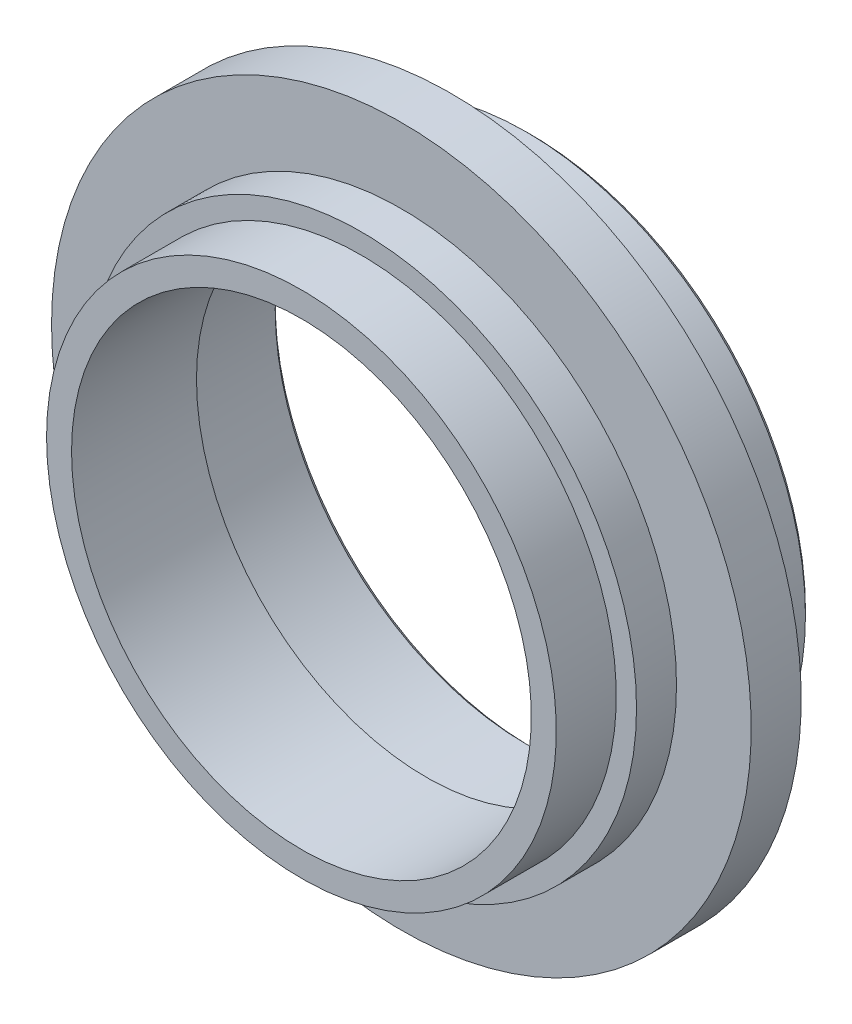
SolidWorks part; units mm, degrees
ref_plane "Front Plane" through (0, 0, 0) normal (0, 0, 1) x (1, 0, 0)
ref_plane "Top Plane" through (0, 0, 0) normal (0, 1, 0) x (1, 0, 0)
ref_plane "Right Plane" through (0, 0, 0) normal (1, 0, 0) x (0, 0, -1)
sketch "Sketch1" plane through (0, 0, 0) normal (0, 1, 0) x (1, 0, 0)
  line L0 (0, 99.2979) -> (0, -58.5521) construction
  line L1 (-100.4208, 0) -> (85.3417, 0) construction
  line L3 (25.125, 23) -> (27.925, 23)
  line L4 (27.925, 23) -> (27.925, 15)
  line L5 (27.925, 15) -> (35, 15)
  line L6 (35, 15) -> (35, 10)
  line L7 (35, 10) -> (27.525, 10)
  line L13 (25.5, 0) -> (23, 0)
  line L16 (25.125, 12.5) -> (23, 12.5)
  line L17 (23, 12.5) -> (23, 0)
  line L18 (25.125, 12.5) -> (25.125, 23)
  line L19 (25.5, 6) -> (27.525, 6)
  line L20 (27.525, 6) -> (27.525, 10)
  line L22 (25.5, 6) -> (25.5, 0)
  dimension "D2" = 2.8
  dimension "D3" = 35
  dimension "D4" = 25.5
  dimension "D6" = 8
  dimension "D7" = 5
  dimension "D8" = 23
  dimension "D12" = 25.125
  dimension "D14" = 2.5
revolve "Revolve1" add sketch "Sketch1" angle 360 about L0
chamfer "Chamfer1" distance 0.5 angle 45 2 edges at (-27.925, 0, -23) (-25.125, 0, -23)
